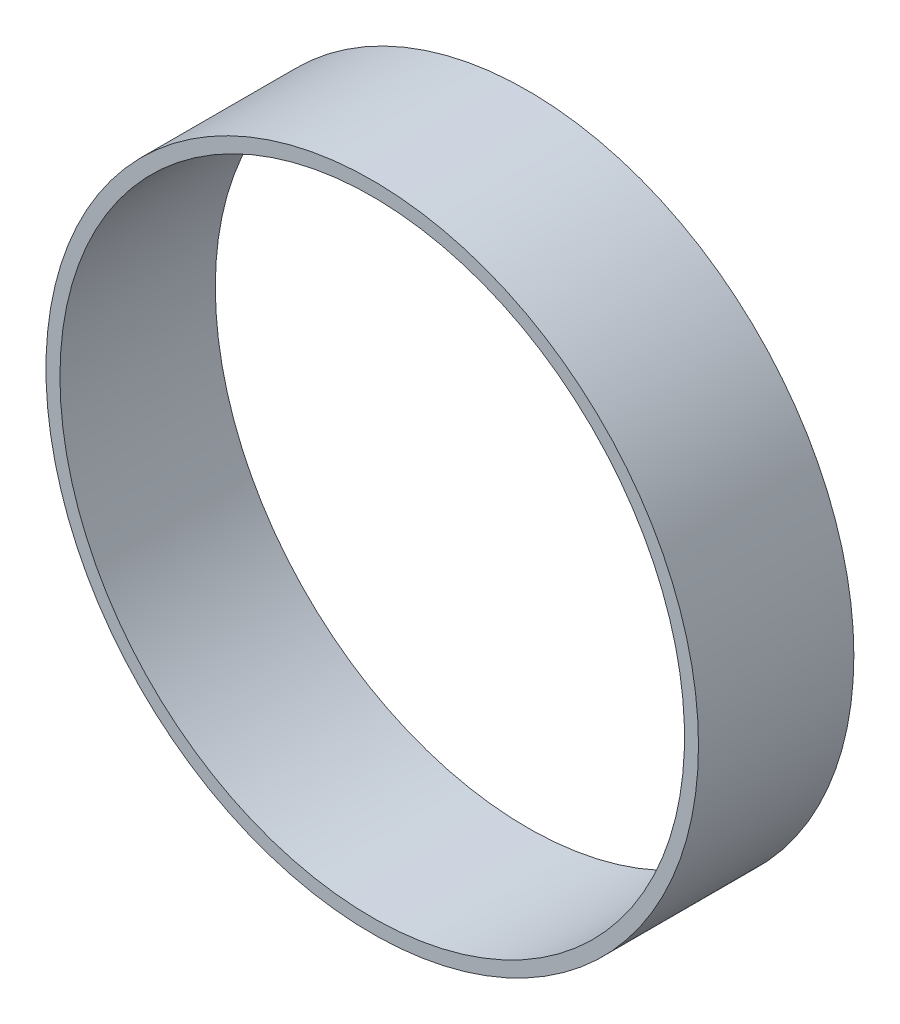
SolidWorks part; units mm, degrees
ref_plane "前视基准面" through (0, 0, 0) normal (0, 0, 1) x (1, 0, 0)
ref_plane "上视基准面" through (0, 0, 0) normal (0, 1, 0) x (1, 0, 0)
ref_plane "右视基准面" through (0, 0, 0) normal (1, 0, 0) x (0, 0, -1)
other "Configuration Table"
sketch "草图1" plane through (0, 0, 0) normal (0, 0, 1) x (1, 0, 0)
  circle A0 centre (0, 0) radius 10.5
  dimension "D1" = 21
extrude "凸台-拉伸1" add sketch "草图1" along normal blind 5
sketch "草图2" plane through (0, 0, 0) normal (0, 0, -1) x (-1, 0, 0)
  circle A0 centre (0, 0) radius 10.05
  dimension "D1" = 20.1
extrude "切除-拉伸1" cut sketch "草图2" against normal blind 5
